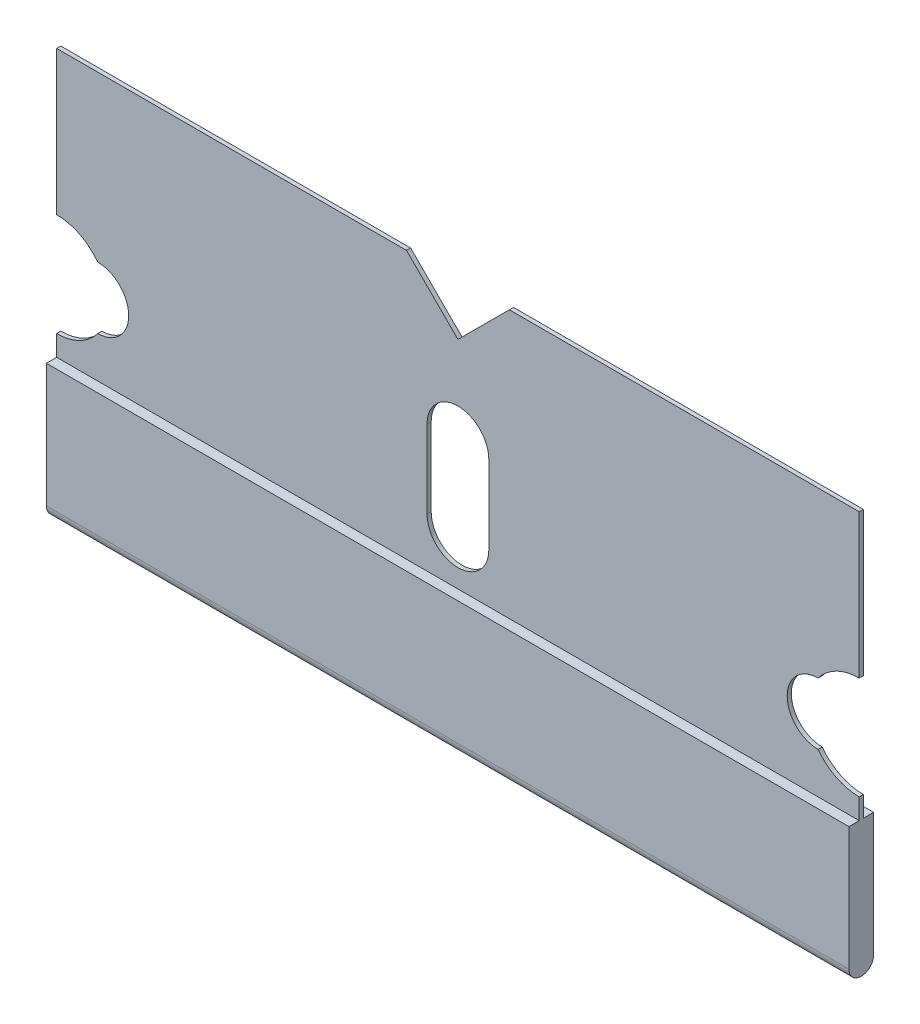
SolidWorks part; units mm, degrees
ref_plane "Front Plane" through (0, 0, 0) normal (0, 0, 1) x (1, 0, 0)
ref_plane "Top Plane" through (0, 0, 0) normal (0, 1, 0) x (1, 0, 0)
ref_plane "Right Plane" through (0, 0, 0) normal (1, 0, 0) x (0, 0, -1)
sketch "Sketch1" plane through (0, 0, 0) normal (0, 0, 1) x (1, 0, 0)
  line L0 (19.5, 19.5) -> (19.5, 4.917) construction
  line L1 (0, 0) -> (39, 0)
  line L2 (0, 0) -> (0, 7.5)
  line L3 (0, 19.5) -> (39, 19.5)
  line L4 (39, 0) -> (39, 7.5)
  line L5 (19.5, 12.7) -> (19.5, 8.9) construction
  line L6 (21, 12.7) -> (21, 8.9)
  line L7 (18, 12.7) -> (18, 8.9)
  line L8 (39, 12.5) -> (39, 19.5)
  line L9 (0, 12.5) -> (0, 19.5)
  arc A0 (21, 12.7) -> (18, 12.7) centre (19.5, 12.7) ccw
  arc A1 (18, 8.9) -> (21, 8.9) centre (19.5, 8.9) ccw
  arc A2 (37, 11.5) -> (37, 8.5) centre (37, 10) ccw
  arc A3 (37, 8.5) -> (39, 7.5) centre (39, 10) ccw
  arc A4 (39, 12.5) -> (37, 11.5) centre (39, 10) ccw
  arc A5 (0, 12.5) -> (2, 11.5) centre (0, 10) cw
  arc A6 (2, 8.5) -> (0, 7.5) centre (0, 10) cw
  arc A7 (2, 11.5) -> (2, 8.5) centre (2, 10) cw
  point P9 (19.5, 10.8)
  dimension "D4" = 1.5
  dimension "D7" = 3
  dimension "D10" = 5
  dimension "D1" = 39
  dimension "D2" = 19.5
  dimension "D5" = 3.8
  dimension "D6" = 6.8
  dimension "D8" = 2
  dimension "D9" = 9.5
  dimension "D11" = 9.5
extrude "Boss-Extrude1" add sketch "Sketch1" along normal blind 0.2
sketch "Sketch2" plane through (39, 0, 0) normal (1, 0, 0) x (0, 0, -1)
  line L0 (0, 0.8474) -> (0.5, 0.8474) construction
  line L1 (-0.7, 0.5) -> (0.5, 0.5) construction
  line L2 (-0.7, 0.5) -> (-0.7, 6.5)
  line L3 (-0.7, 6.5) -> (-0.2, 6.5)
  line L4 (0.5, 0.5) -> (0.5, 6.5)
  line L5 (0, 0) -> (0, 7.5) construction
  line L6 (-0.2, 0.8474) -> (-0.7, 0.8474) construction
  line L7 (-0.2, 0) -> (-0.2, 7.5) construction
  line L8 (0, 6.5) -> (0.5, 6.5)
  line L9 (-0.2, 0) -> (0, 0)
  line L10 (-0.2, 0) -> (-0.2, 6.5)
  line L12 (0, 0) -> (0, 6.5)
  arc A0 (-0.7, 0.5) -> (0.5, 0.5) centre (-0.1, 0.5) ccw
  point P17 (-0.1, 0)
  dimension "D1" = 1.2
  dimension "D2" = 6
  dimension "D3" = 0.5
extrude "Boss-Extrude2" add sketch "Sketch2" against normal up to surface (39 mm away) up to face at (0, 3.75, 0.1)
sketch "Sketch3" plane through (0, 0, 0.2) normal (0, 0, 1) x (1, 0, 0)
  line L0 (19.5, 19.5) -> (19.5, 11.3017) construction
  line L1 (39, 19.5) -> (0, 19.5) construction
  line L2 (17, 19.5) -> (19.5, 17.0029)
  line L3 (22, 19.5) -> (19.5, 17.0029)
  line L4 (17, 19.5) -> (17, 22.5397)
  line L5 (17, 22.5397) -> (22, 22.5397)
  line L6 (22, 22.5397) -> (22, 19.5)
  dimension "D1" = 2.5
  dimension "D2" = 2.4971
extrude "Cut-Extrude1" cut sketch "Sketch3" against normal blind 10
